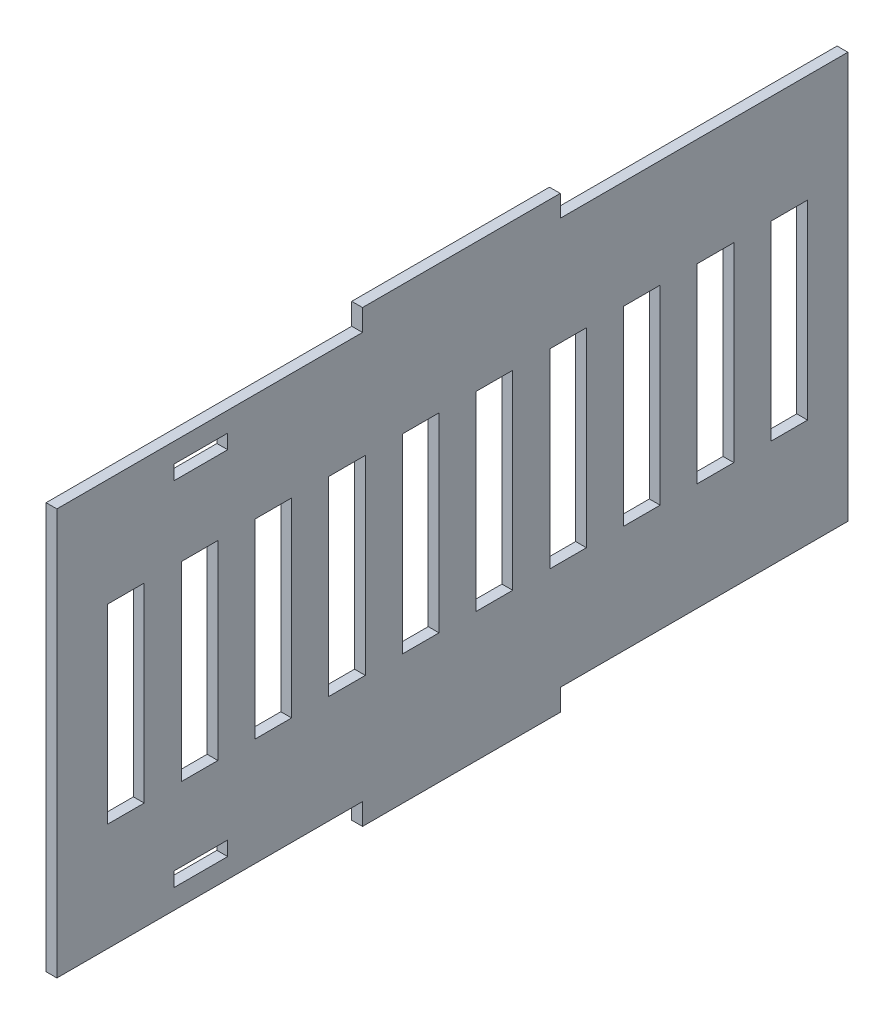
SolidWorks part; units mm, degrees
ref_plane "Front Plane" through (0, 0, 0) normal (0, 0, 1) x (1, 0, 0)
ref_plane "Top Plane" through (0, 0, 0) normal (0, 1, 0) x (1, 0, 0)
ref_plane "Right Plane" through (0, 0, 0) normal (1, 0, 0) x (0, 0, -1)
sketch "Sketch2" plane through (0, 0, 0) normal (1, 0, 0) x (0, 0, -1)
  line L0 (0, 0) -> (-220, 0)
  line L1 (-220, 0) -> (-220, 125)
  line L2 (-220, 125) -> (0, 125)
  line L3 (0, 125) -> (0, 0)
  dimension "D1" = 220
  dimension "D2" = 125
extrude "Boss-Extrude1" add sketch "Sketch2" along normal blind 3
sketch "Sketch3" plane through (0, 0, 0) normal (-1, 0, 0) x (0, 0, 1)
  line L0 (0, 119) -> (80, 119)
  line L1 (0, 0) -> (0, 125) construction
  line L2 (220, 125) -> (220, 0) construction
  line L3 (0, 6) -> (80, 6)
  line L4 (80, 125) -> (80, 119)
  line L5 (0, 125) -> (220, 125) construction
  line L6 (220, 0) -> (0, 0) construction
  line L7 (135, 125) -> (135, 119)
  line L8 (80, 6) -> (80, 0)
  line L9 (135, 119) -> (220, 119)
  line L10 (135, 6) -> (135, 0)
  line L11 (135, 6) -> (220, 6)
  line L12 (0, 119) -> (0, 125)
  line L13 (0, 125) -> (80, 125)
  line L14 (220, 125) -> (135, 125)
  line L15 (220, 125) -> (220, 119)
  line L16 (220, 6) -> (220, 0)
  line L17 (220, 0) -> (135, 0)
  line L18 (80, 0) -> (0, 0)
  line L19 (0, 0) -> (0, 6)
  dimension "D1" = 80
  dimension "D2" = 85
  dimension "D3" = 6
  dimension "D4" = 6
extrude "Cut-Extrude1" cut sketch "Sketch3" against normal blind 3
sketch "Sketch4" plane through (0, 0, 0) normal (-1, 0, 0) x (0, 0, 1)
  line L0 (0, 119) -> (80, 119) construction
  line L1 (11.2201, 89) -> (21.4101, 89)
  line L2 (11.2201, 89) -> (11.2201, 36)
  line L3 (11.2201, 36) -> (21.4101, 36)
  line L4 (21.4101, 89) -> (21.4101, 36)
  line L5 (80, 6) -> (0, 6) construction
  line L6 (41.9101, 89) -> (41.9101, 36)
  line L7 (31.7201, 89) -> (31.7201, 36)
  line L8 (31.7201, 89) -> (41.9101, 89)
  line L9 (31.7201, 36) -> (41.9101, 36)
  line L10 (62.4101, 89) -> (62.4101, 36)
  line L11 (52.2201, 89) -> (52.2201, 36)
  line L12 (52.2201, 89) -> (62.4101, 89)
  line L13 (52.2201, 36) -> (62.4101, 36)
  line L14 (82.9101, 89) -> (82.9101, 36)
  line L15 (72.7201, 89) -> (72.7201, 36)
  line L16 (72.7201, 89) -> (82.9101, 89)
  line L17 (72.7201, 36) -> (82.9101, 36)
  line L18 (103.4101, 89) -> (103.4101, 36)
  line L19 (93.2201, 89) -> (93.2201, 36)
  line L20 (93.2201, 89) -> (103.4101, 89)
  line L21 (93.2201, 36) -> (103.4101, 36)
  line L22 (123.9101, 89) -> (123.9101, 36)
  line L23 (113.7201, 89) -> (113.7201, 36)
  line L24 (113.7201, 89) -> (123.9101, 89)
  line L25 (113.7201, 36) -> (123.9101, 36)
  line L26 (144.4101, 89) -> (144.4101, 36)
  line L27 (134.2201, 89) -> (134.2201, 36)
  line L28 (134.2201, 89) -> (144.4101, 89)
  line L29 (134.2201, 36) -> (144.4101, 36)
  line L30 (164.9101, 89) -> (164.9101, 36)
  line L31 (154.7201, 89) -> (154.7201, 36)
  line L32 (154.7201, 89) -> (164.9101, 89)
  line L33 (154.7201, 36) -> (164.9101, 36)
  line L34 (185.4101, 89) -> (185.4101, 36)
  line L35 (175.2201, 89) -> (175.2201, 36)
  line L36 (175.2201, 89) -> (185.4101, 89)
  line L37 (175.2201, 36) -> (185.4101, 36)
  line L38 (205.9101, 89) -> (205.9101, 36)
  line L39 (195.7201, 89) -> (195.7201, 36)
  line L40 (195.7201, 89) -> (205.9101, 89)
  line L41 (195.7201, 36) -> (205.9101, 36)
  dimension "D1" = 30
  dimension "D2" = 30
  dimension "D3" = 10
extrude "Cut-Extrude2" cut sketch "Sketch4" against normal blind 3
sketch "Sketch6" plane through (0, 0, 0) normal (-1, 0, 0) x (0, 0, 1)
  line L0 (220, 119) -> (220, 6) construction
  line L1 (172.5, 113.5) -> (187.5, 113.5)
  line L2 (172.5, 113.5) -> (172.5, 109.5)
  line L3 (172.5, 109.5) -> (187.5, 109.5)
  line L4 (187.5, 113.5) -> (187.5, 109.5)
  line L5 (180, 109.5) -> (180, 113.5) construction
  line L6 (172.5, 111.5) -> (187.5, 111.5) construction
  line L7 (135, 119) -> (220, 119) construction
  line L8 (220, 62.5) -> (0, 62.5) construction
  line L9 (0, 6) -> (0, 119) construction
  line L10 (172.5, 13.5) -> (187.5, 13.5) construction
  line L11 (180, 15.5) -> (180, 11.5) construction
  line L12 (187.5, 11.5) -> (187.5, 15.5)
  line L13 (172.5, 15.5) -> (187.5, 15.5)
  line L14 (172.5, 11.5) -> (172.5, 15.5)
  line L15 (172.5, 11.5) -> (187.5, 11.5)
  point P0 (180, 111.5)
  point P20 (180, 13.5)
  dimension "D1" = 40
  dimension "D2" = 4
  dimension "D3" = 15
  dimension "D4" = 7.5
extrude "Cut-Extrude3" cut sketch "Sketch6" against normal blind 10
